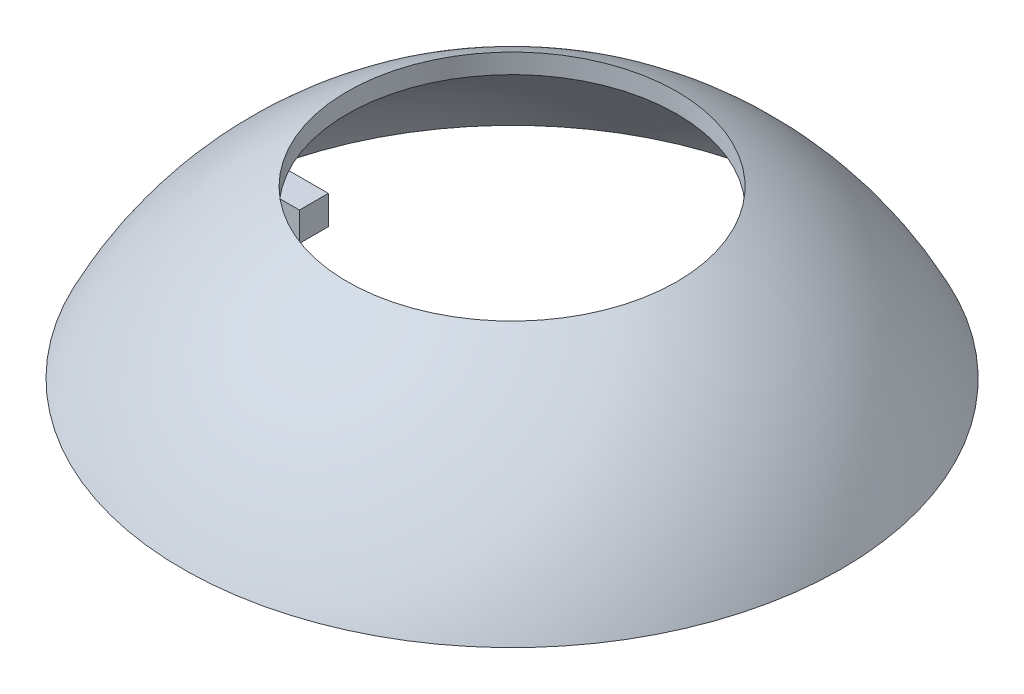
SolidWorks part; units mm, degrees
ref_plane "Alzado" through (0, 0, 0) normal (0, 0, 1) x (1, 0, 0)
ref_plane "Planta" through (0, 0, 0) normal (0, 1, 0) x (1, 0, 0)
ref_plane "Vista lateral" through (0, 0, 0) normal (1, 0, 0) x (0, 0, -1)
sketch "Croquis2" plane through (0, 0, 0) normal (0, 0, 1) x (1, 0, 0)
  line L3 (57, 27.9866) -> (53.6377, 27.9866)
  line L4 (0, 10.0584) -> (0, 27.9866) construction
  line L7 (28.5, 53.3667) -> (28.5, 56.745)
  arc A0 (57, 27.9866) -> (28.5, 56.745) centre (0, 0) ccw
  arc A1 (53.6377, 27.9866) -> (28.5, 53.3667) centre (0, 0) ccw
  circle A2 centre (0, 0) radius 63.5 construction
  circle A3 centre (0, 0) radius 60.5 construction
  point P9 (0, 10.0584)
  point P16 (0, 27.9866)
  dimension "D1" = 127
  dimension "D2" = 3
revolve "Revolución2" add sketch "Croquis2" angle 360 about L4
sketch "Croquis3" plane through (0, 27.9866, 0) normal (0, -1, 0) x (1, 0, 0)
  line L0 (38.6301, 1.8489) -> (49.3798, 1.8489)
  line L2 (-38.6301, -6.8489) -> (-38.6301, -1.8489) construction
  line L3 (-38.6301, 8.1511) -> (-53.0147, 8.1511)
  line L4 (-53.1986, -6.8489) -> (-38.6301, -6.8489)
  line L5 (-38.6301, -6.8489) -> (-38.6301, -1.8489)
  line L6 (-38.6301, -1.8489) -> (-49.3798, -1.8489)
  line L8 (-49.3798, -1.8489) -> (-49.3798, 3.1511)
  line L9 (-49.3798, 3.1511) -> (-38.6301, 3.1511)
  line L10 (-38.6301, 3.1511) -> (-38.6301, 8.1511) construction
  line L11 (-38.6301, 3.1511) -> (-38.6301, 8.1511)
  line L12 (49.3798, 1.8489) -> (49.3798, -3.1511)
  line L13 (49.3798, -3.1511) -> (38.6301, -3.1511)
  line L14 (38.6301, -3.1511) -> (38.6301, -8.1511)
  line L15 (38.6301, -8.1511) -> (53.0147, -8.1511)
  line L16 (53.1986, 6.8489) -> (38.6301, 6.8489)
  line L17 (38.6301, 6.8489) -> (38.6301, 1.8489)
  circle A0 centre (0, 0) radius 53.6377 construction
  arc A1 (-53.1986, -6.8489) -> (-53.0147, 8.1511) centre (0, 0) cw
  arc A2 (53.1986, 6.8489) -> (53.0147, -8.1511) centre (0, 0) cw
  point P9 (-38.6301, 0.6511)
  point P12 (-38.6301, 0.6511)
  point P24 (0, 0)
  dimension "D3" = 2
  dimension "D1" = 5
  dimension "D2" = 15
extrude "Saliente-Extruir1" add sketch "Croquis3" against normal blind 5
equation "\"D3quis1\" = \"D3quis1\""
